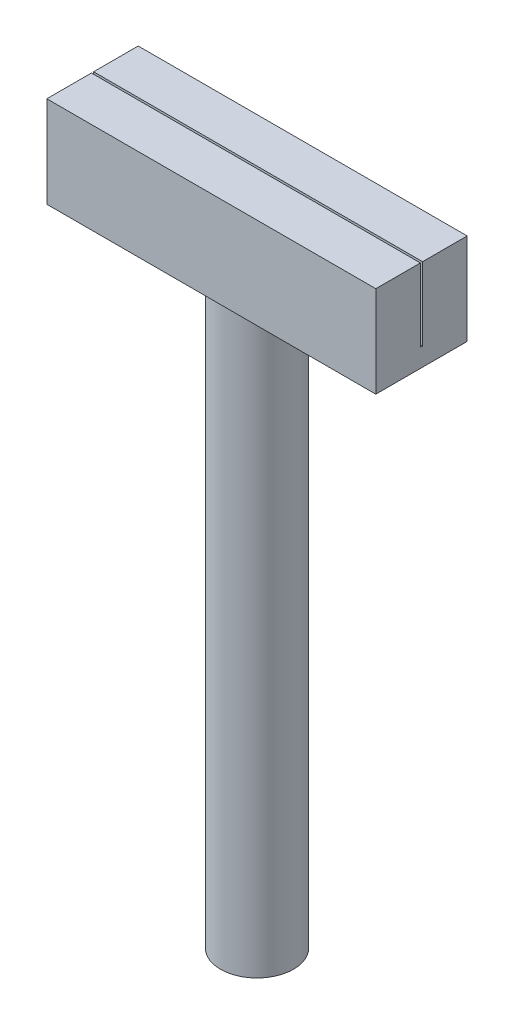
SolidWorks part; units mm, degrees
ref_plane "Front Plane" through (0, 0, 0) normal (0, 0, 1) x (1, 0, 0)
ref_plane "Top Plane" through (0, 0, 0) normal (0, 1, 0) x (1, 0, 0)
ref_plane "Right Plane" through (0, 0, 0) normal (1, 0, 0) x (0, 0, -1)
sketch "Sketch1" plane through (0, 0, 0) normal (0, 1, 0) x (1, 0, 0)
  circle A0 centre (0, 0) radius 5
  dimension "D1" = 10
extrude "Boss-Extrude1" add sketch "Sketch1" along normal blind 80
sketch "Sketch2" plane through (0, 0, 0) normal (0, 1, 0) x (1, 0, 0)
  line L1 (-22.5, 6.25) -> (22.5, 6.25)
  line L2 (-22.5, 6.25) -> (-22.5, -6.25)
  line L3 (-22.5, -6.25) -> (22.5, -6.25)
  line L4 (22.5, 6.25) -> (22.5, -6.25)
  line L5 (-22.5, 6.25) -> (22.5, -6.25) construction
  line L6 (-22.5, -6.25) -> (22.5, 6.25) construction
  point P0 (0, 0)
  dimension "D1" = 45
  dimension "D2" = 12.5
extrude "Boss-Extrude2" add sketch "Sketch2" along normal blind 12.5 from surface at 80 starting at face at (0, 80, 5)
sketch "Sketch3" plane through (0, 0, 0) normal (1, 0, 0) x (0, 0, -1)
  line L0 (0, 92.5) -> (0, 80) construction
  line L1 (6.25, 92.5) -> (-6.25, 92.5) construction
  line L2 (-5, 80) -> (5, 80) construction
  line L3 (-0.15, 92.5) -> (-0.15, 82.5)
  line L4 (-0.15, 82.5) -> (0.15, 82.5)
  line L6 (-0.15, 92.5) -> (0.15, 92.5)
  line L7 (0.15, 92.5) -> (0.15, 82.5)
  point P10 (0, 82.5)
  dimension "D1" = 0.15
  dimension "D2" = 10
extrude "Cut-Extrude1" cut sketch "Sketch3" against normal through all both and the other way through all
